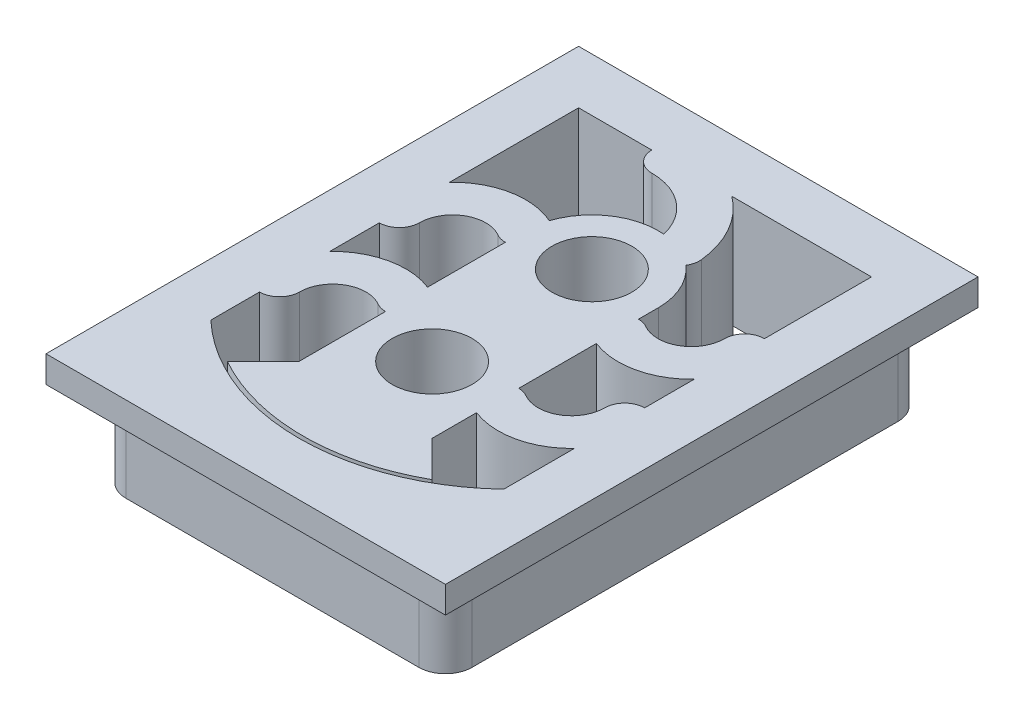
SolidWorks part; units mm, degrees
ref_plane "Front Plane" through (0, 0, 0) normal (0, 0, 1) x (1, 0, 0)
ref_plane "Top Plane" through (0, 0, 0) normal (0, 1, 0) x (1, 0, 0)
ref_plane "Right Plane" through (0, 0, 0) normal (1, 0, 0) x (0, 0, -1)
sketch "Sketch1" plane through (0, 0, 0) normal (0, 1, 0) x (1, 0, 0)
  line L1 (-6.5, -9) -> (6.5, -9)
  line L2 (-6.5, -9) -> (-6.5, 9)
  line L3 (-6.5, 9) -> (6.5, 9)
  line L4 (6.5, -9) -> (6.5, 9)
  line L5 (-6.5, -9) -> (6.5, 9) construction
  line L6 (-6.5, 9) -> (6.5, -9) construction
  point P0 (0, 0)
  dimension "D1" = 18
  dimension "D2" = 13
extrude "Boss-Extrude1" add sketch "Sketch1" along normal blind 3.2
sketch "Sketch2" plane through (0, 3.2, 0) normal (0, 1, 0) x (1, 0, 0)
  line L8 (7.5, -10) -> (7.5, 10)
  line L9 (7.5, 10) -> (-7.5, 10)
  line L10 (-7.5, 10) -> (-7.5, -10)
  line L11 (-7.5, -10) -> (7.5, -10)
  line L12 (7.5, -10) -> (7.5, 10)
  line L13 (7.5, 10) -> (-7.5, 10)
  line L14 (-7.5, 10) -> (-7.5, -10)
  line L15 (-7.5, -10) -> (7.5, -10)
  dimension "D1" = 1
extrude "Boss-Extrude2" add sketch "Sketch2" along normal blind 1
sketch "Sketch4" plane through (0, 0, 0) normal (0, -1, 0) x (1, 0, 0)
  line L0 (-3.8443, 6.8443) -> (-2.5, 5.5)
  line L1 (3.8443, 6.8443) -> (2.5, 5.5)
  line L4 (0, -3) -> (0, 3)
  line L6 (2.5, -5.5) -> (-2.5, -5.5)
  line L7 (2.5, -5.5) -> (2.5, 5.5)
  line L8 (5.5, -8) -> (5.5, 8)
  line L9 (5.5, 8) -> (-5.5, 8)
  line L10 (-5.5, 8) -> (-5.5, -8)
  line L11 (-5.5, -8) -> (5.5, -8)
  line L12 (5.5, -8) -> (5.5, 8)
  line L13 (5.5, 8) -> (-5.5, 8)
  line L14 (-5.5, 8) -> (-5.5, -8)
  line L15 (-5.5, -8) -> (5.5, -8)
  line L16 (2.5, 5.5) -> (-2.5, 5.5)
  line L17 (-2.5, -5.5) -> (-2.5, 5.5)
  line L18 (2.5, -5.5) -> (-2.5, 5.5) construction
  line L19 (2.5, 5.5) -> (-2.5, -5.5) construction
  circle A0 centre (0, 3) radius 1.5
  circle A1 centre (0, -3) radius 1.5
  circle A3 centre (0, -3) radius 2.5
  arc A4 (-2.5, 3) -> (-5.5, 1.2679) centre (-3.5, 1.2679) ccw
  arc A5 (2.5, 1.5) -> (5.5, 3.2321) centre (3.5, 3.2321) ccw
  arc A6 (2.5, -3) -> (5.5, -1.2679) centre (3.5, -1.2679) ccw
  arc A7 (-2.5, -1.5) -> (-5.5, -3.2321) centre (-3.5, -3.2321) ccw
  arc A9 (-1, -5.2913) -> (2, -8) centre (2, -4.9843) ccw
  arc A11 (3.8443, 6.8443) -> (-3.8443, 6.8443) centre (0, 0) ccw
  arc A12 (0, 8) -> (-5.5, 5.8095) centre (0, 0) ccw
  arc A13 (0, 8) -> (5.5, 5.8095) centre (0, 0) cw
  arc A14 (-2.125, -0.8505) -> (-6.25, -3.2321) centre (-3.5, -3.2321) ccw
  arc A15 (-2.125, 3.6495) -> (-6.25, 1.2679) centre (-3.5, 1.2679) ccw
  arc A16 (2.125, 0.8505) -> (6.25, 3.2321) centre (3.5, 3.2321) ccw
  arc A17 (2.125, -3.6495) -> (6.25, -1.2679) centre (3.5, -1.2679) ccw
  arc A18 (-2.875, -2.1495) -> (-4.75, -3.2321) centre (-3.5, -3.2321) ccw
  arc A19 (-2.875, 2.3505) -> (-4.75, 1.2679) centre (-3.5, 1.2679) ccw
  arc A20 (2.875, 2.1495) -> (4.75, 3.2321) centre (3.5, 3.2321) ccw
  arc A21 (2.875, -2.3505) -> (4.75, -1.2679) centre (3.5, -1.2679) ccw
  arc A22 (-2.125, -0.8505) -> (-2.875, -2.1495) centre (-2.5, -1.5) cw
  arc A23 (-6.25, -3.2321) -> (-4.75, -3.2321) centre (-5.5, -3.2321) ccw
  arc A24 (-2.125, 3.6495) -> (-2.875, 2.3505) centre (-2.5, 3) cw
  arc A25 (-6.25, 1.2679) -> (-4.75, 1.2679) centre (-5.5, 1.2679) ccw
  arc A26 (2.125, 0.8505) -> (2.875, 2.1495) centre (2.5, 1.5) cw
  arc A27 (6.25, 3.2321) -> (4.75, 3.2321) centre (5.5, 3.2321) ccw
  arc A28 (2.125, -3.6495) -> (2.875, -2.3505) centre (2.5, -3) cw
  arc A29 (6.25, -1.2679) -> (4.75, -1.2679) centre (5.5, -1.2679) ccw
  arc A31 (-1.7461, -5.3676) -> (2, -8.75) centre (2, -4.9843) ccw
  arc A33 (-0.2539, -5.2149) -> (2, -7.25) centre (2, -4.9843) ccw
  arc A36 (-1.7461, -5.3676) -> (-0.2539, -5.2149) centre (-1, -5.2913) cw
  arc A37 (2, -8.75) -> (2, -7.25) centre (2, -8) ccw
  point P3 (0, 0)
  point P5 (0, 0)
  dimension "D3" = 3
  dimension "D6" = 7.85
  dimension "D8" = 4.5
  dimension "D7" = 2
  dimension "D13" = 135
  dimension "D14" = 0.75
  dimension "D2" = 6
  dimension "D4" = 11
  dimension "D5" = 5
  dimension "D9" = 4.5
  dimension "D10" = 4.5
  dimension "D11" = 3.5
  dimension "D1" = 1
  dimension "D15" = 0.75
  dimension "D16" = 0.75
  dimension "D17" = 0.75
extrude "Cut-Extrude2" cut sketch "Sketch4" against normal through all
fillet "Fillet1" radius 1 4 edges at (-6.5, 1.6, -9) (6.5, 1.6, -9) (6.5, 1.6, 9) (-6.5, 1.6, 9)
mirror "Mirror2" about plane through (7.5, 4.2, 10) normal (-1, 0, 0) of bodies 107
delete or keep bodies "Body-Delete/Keep 2" type keep bodies bodies 111
mirror "Mirror1" [suppressed]
delete or keep bodies "Body-Delete/Keep 1" [suppressed] type keep bodies bodies 104
